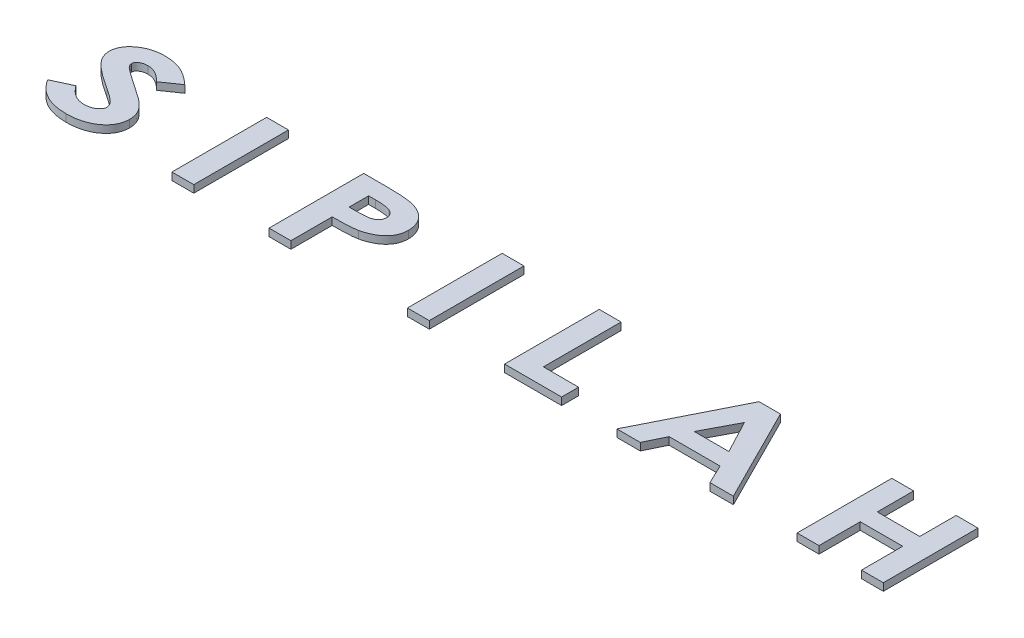
SolidWorks part; units mm, degrees
ref_plane "Front Plane" through (0, 0, 0) normal (0, 0, 1) x (1, 0, 0)
ref_plane "Top Plane" through (0, 0, 0) normal (0, 1, 0) x (1, 0, 0)
ref_plane "Right Plane" through (0, 0, 0) normal (1, 0, 0) x (0, 0, -1)
sketch "Sketch1" plane through (0, 0, 0) normal (0, 1, 0) x (1, 0, 0)
  line L0 (-38, 0) -> (38, 0) construction
  text T0 "<b>S I P I L A H </b>" font "Century Gothic" height in points 24
  point P4 (0, 0)
  dimension "D1" = 76
extrude "Boss-Extrude1" add sketch "Sketch1" along normal blind 0.5
